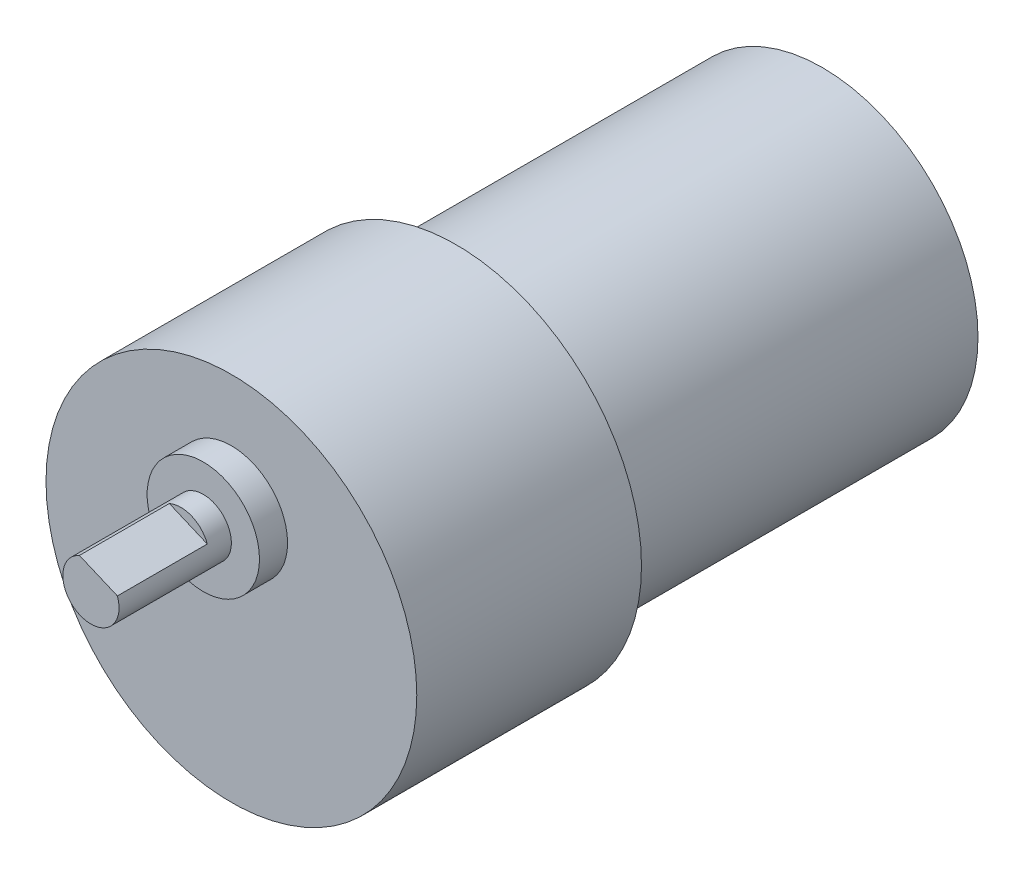
SolidWorks part; units mm, degrees
ref_plane "Front Plane" through (0, 0, 0) normal (0, 0, 1) x (1, 0, 0)
ref_plane "Top Plane" through (0, 0, 0) normal (0, 1, 0) x (1, 0, 0)
ref_plane "Right Plane" through (0, 0, 0) normal (1, 0, 0) x (0, 0, -1)
sketch "Sketch1" plane through (0, 0, 0) normal (0, 0, 1) x (1, 0, 0)
  circle A0 centre (0, 0) radius 16.5
  dimension "D1" = 33
extrude "Boss-Extrude1" add sketch "Sketch1" along normal blind 20
sketch "Sketch2" plane through (0, 0, 0) normal (0, 0, -1) x (-1, 0, 0)
  circle A0 centre (0, 0) radius 13.85
  dimension "D1" = 27.7
extrude "Boss-Extrude2" add sketch "Sketch2" along normal blind 32.6
sketch "Sketch3" plane through (0, 0, -32.6) normal (0, 0, -1) x (-1, 0, 0)
  circle A0 centre (0, 0) radius 5
  dimension "D1" = 10
extrude "Boss-Extrude3" add sketch "Sketch3" along normal blind 2.2
sketch "Sketch4" plane through (0, 0, -34.8) normal (0, 0, -1) x (-1, 0, 0)
  circle A0 centre (0, 0) radius 1.15
  dimension "D1" = 2.3
extrude "Boss-Extrude4" add sketch "Sketch4" along normal blind 3.3
sketch "Sketch5" plane through (0, 0, 20) normal (0, 0, 1) x (1, 0, 0)
  line L0 (0, 16.5) -> (0, -16.5) construction
  line L1 (-16.5, 0) -> (16.5, 0) construction
  circle A0 centre (0, 0) radius 16.5 construction
  circle A1 centre (0, 6) radius 5
  dimension "D2" = 10
  dimension "D1" = 6
extrude "Boss-Extrude5" add sketch "Sketch5" along normal blind 2.5
sketch "Sketch6" plane through (0, 0, 22.5) normal (0, 0, 1) x (1, 0, 0)
  circle A0 centre (0, 6) radius 2.5
  dimension "D1" = 5
extrude "Boss-Extrude6" add sketch "Sketch6" along normal blind 10
sketch "Sketch7" plane through (0, 0, 32.5) normal (0, 0, 1) x (1, 0, 0)
  line L0 (-1.0242, 8.2806) -> (2.3522, 6.8469)
  line L1 (0, 8.5) -> (0, 3.5) construction
  circle A0 centre (0, 6) radius 2.5 construction
  arc A1 (-1.0242, 8.2806) -> (2.3522, 6.8469) centre (0, 6) cw
  dimension "D1" = 4
extrude "Cut-Extrude1" cut sketch "Sketch7" against normal blind 8
equation "\"motor offset\"=6mm"
equation "\"thickness0.25\"=0.225in"
equation "\"thickness0.125\"=0.122in"
